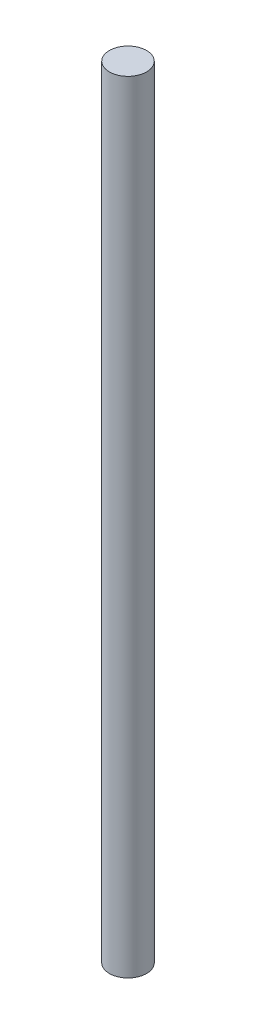
SolidWorks part; units mm, degrees
ref_plane "Plano frontal" through (0, 0, 0) normal (0, 0, 1) x (1, 0, 0)
ref_plane "Plano superior" through (0, 0, 0) normal (0, 1, 0) x (1, 0, 0)
ref_plane "Plano direito" through (0, 0, 0) normal (1, 0, 0) x (0, 0, -1)
sketch "Esboço1" plane through (0, 0, 0) normal (0, 1, 0) x (1, 0, 0)
  circle A0 centre (0, 0) radius 10
  dimension "D1" = 20
extrude "Ressalto-extrusão1" add sketch "Esboço1" along normal blind 420
